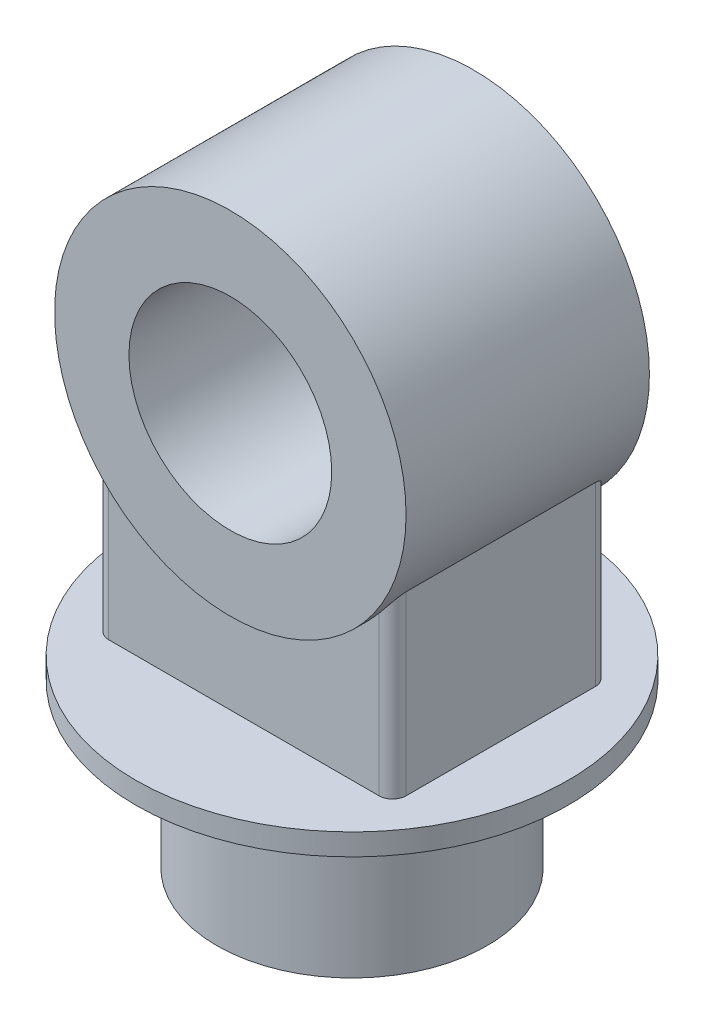
SolidWorks part; units mm, degrees
ref_plane "Front Plane" through (0, 0, 0) normal (0, 0, 1) x (1, 0, 0)
ref_plane "Top Plane" through (0, 0, 0) normal (0, 1, 0) x (1, 0, 0)
ref_plane "Right Plane" through (0, 0, 0) normal (1, 0, 0) x (0, 0, -1)
sketch "Sketch1" plane through (0, 0, 0) normal (0, 1, 0) x (1, 0, 0)
  circle A0 centre (0, 0) radius 100
  dimension "D1" = 200
extrude "Boss-Extrude1" add sketch "Sketch1" along normal blind 120
sketch "Sketch2" plane through (0, 120, 0) normal (0, 1, 0) x (1, 0, 0)
  circle A0 centre (0, 0) radius 160
  dimension "D1" = 320
extrude "Boss-Extrude2" add sketch "Sketch2" along normal blind 16
sketch "Sketch3" plane through (0, 0, 0) normal (0, 0, 1) x (1, 0, 0)
  line L0 (0, 0) -> (0, 7.5859)
  line L2 (160, 136) -> (-160, 136) construction
  circle A0 centre (0, 336) radius 75
  circle A1 centre (0, 336) radius 130
  dimension "D1" = 150
  dimension "D2" = 260
  dimension "D3" = 200
extrude "Boss-Extrude3" add sketch "Sketch3" along normal mid plane 180 separate body contours A1 A0
sketch "Sketch4" plane through (0, 136, 0) normal (0, 1, 0) x (1, 0, 0)
  line L1 (-110, 80) -> (110, 80)
  line L2 (-110, 80) -> (-110, -80)
  line L3 (-110, -80) -> (110, -80)
  line L4 (110, 80) -> (110, -80)
  line L5 (-110, 80) -> (110, -80) construction
  line L6 (-110, -80) -> (110, 80) construction
  point P0 (0, 0)
  dimension "D1" = 160
  dimension "D2" = 220
extrude "Boss-Extrude4" add sketch "Sketch4" along normal up to next
fillet "Fillet1" radius 10 4 edges at (110, 201.359, 80) (-110, 201.359, 80) (110, 201.359, -80) (-110, 201.359, -80)
